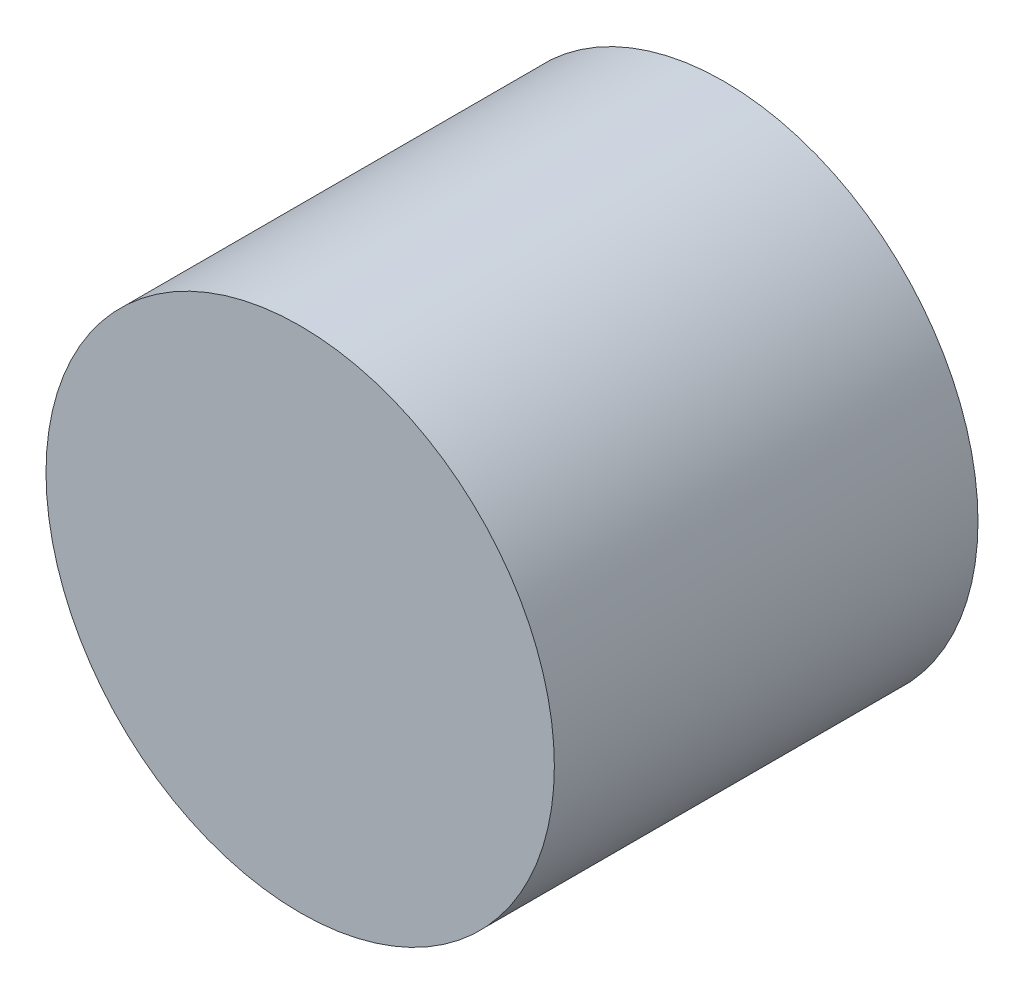
SolidWorks part; units mm, degrees
ref_plane "Plan de face" through (0, 0, 0) normal (0, 0, 1) x (1, 0, 0)
ref_plane "Plan de dessus" through (0, 0, 0) normal (0, 1, 0) x (1, 0, 0)
ref_plane "Plan de droite" through (0, 0, 0) normal (1, 0, 0) x (0, 0, -1)
sketch "Esquisse1" plane through (0, 0, 0) normal (0, 0, 1) x (1, 0, 0)
  line L0 (0, -1.5) -> (0, 1) construction
  line L1 (0, 1) -> (-1.118, 1)
  line L2 (-1.118, 1) -> (1.118, 1)
  circle A0 centre (0, 0) radius 1.5
  dimension "D1" = 3
  dimension "D2" = 2.5
extrude "Boss.-Extru.1" add sketch "Esquisse1" along normal blind 5 contours A0 L0 L1 | L0 A0 L2
sketch "Esquisse2" plane through (0, 0, 5) normal (0, 0, 1) x (1, 0, 0)
  circle A0 centre (0, 0) radius 1.5
  dimension "D1" = 3
extrude "Boss.-Extru.2" add sketch "Esquisse2" along normal blind 2
sketch "Esquisse3" plane through (0, 0, 7) normal (0, 0, 1) x (1, 0, 0)
  circle A0 centre (0, 0.1312) radius 15
  dimension "D1" = 30
extrude "Boss.-Extru.3" add sketch "Esquisse3" along normal blind 25
